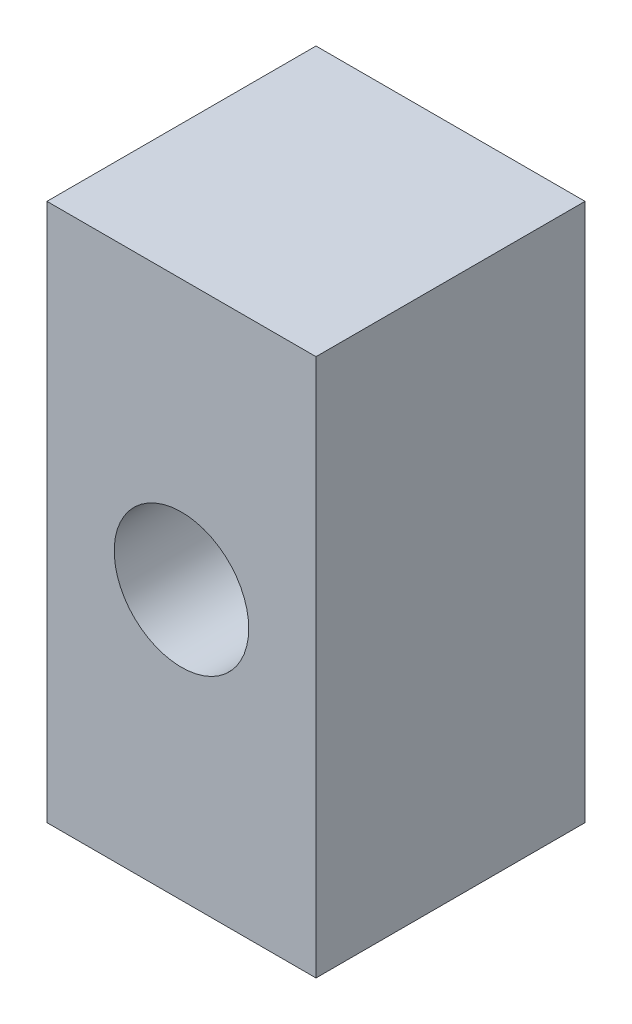
SolidWorks part; units mm, degrees
material "1060 Alloy"
ref_plane "Front Plane" through (0, 0, 0) normal (0, 0, 1) x (1, 0, 0)
ref_plane "Top Plane" through (0, 0, 0) normal (0, 1, 0) x (1, 0, 0)
ref_plane "Right Plane" through (0, 0, 0) normal (1, 0, 0) x (0, 0, -1)
sketch "Sketch2" plane through (0, 0, 0) normal (0, 0, 1) x (1, 0, 0)
  line L1 (-43.7731, 40.0459) -> (7.0269, 40.0459)
  line L2 (-43.7731, 40.0459) -> (-43.7731, -61.5541)
  line L3 (-43.7731, -61.5541) -> (7.0269, -61.5541)
  line L4 (7.0269, 40.0459) -> (7.0269, -61.5541)
  circle A0 centre (-18.3731, -10.7541) radius 12.7
  dimension "D5" = 25.4
  dimension "D1" = 101.6
  dimension "D2" = 50.8
  dimension "D3" = 25.4
  dimension "D4" = 50.8
extrude "Boss-Extrude1" add sketch "Sketch2" along normal blind 50.8
